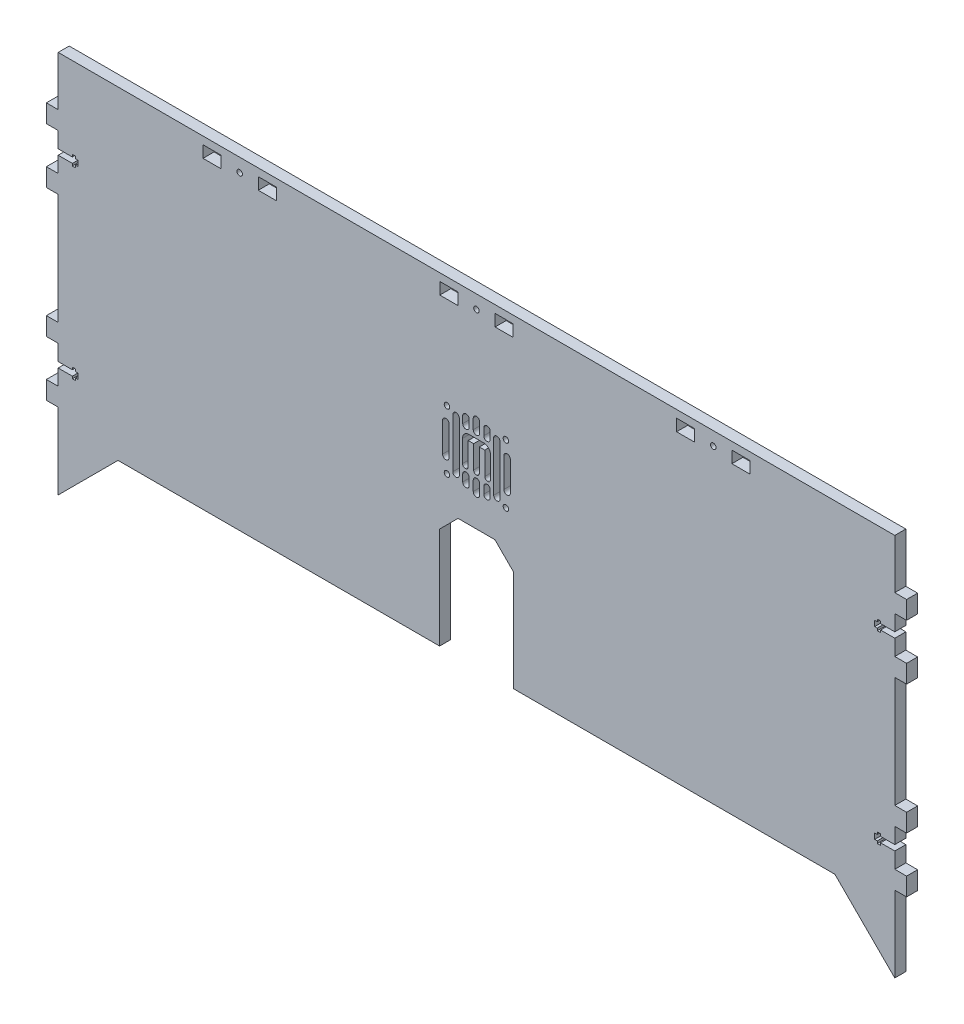
SolidWorks part; units mm, degrees
material "Acrylic (Medium-high impact)"
ref_plane "Front Plane" through (0, 0, 0) normal (0, 0, 1) x (1, 0, 0)
ref_plane "Top Plane" through (0, 0, 0) normal (0, 1, 0) x (1, 0, 0)
ref_plane "Right Plane" through (0, 0, 0) normal (1, 0, 0) x (0, 0, -1)
sketch "Sketch1" plane through (0, 0, 0) normal (0, 0, 1) x (1, 0, 0)
  line L0 (-200.4146, -68.906) -> (-25.9097, -68.906)
  line L1 (-200.4146, -68.906) -> (-232.9097, -101.4011)
  line L2 (-232.9097, 106.5989) -> (-232.9097, 79.6889)
  line L3 (-232.9097, 106.5989) -> (-117.9097, 106.5989)
  line L4 (106.0903, 106.5989) -> (221.0903, 106.5989)
  line L5 (221.0903, 39.8889) -> (221.0903, -20.3111)
  line L6 (-225.2097, 58.2882) -> (-232.9097, 58.2882)
  line L7 (-232.9097, 69.8889) -> (-232.9097, 61.2895)
  line L8 (-239.3097, 49.6889) -> (-239.3097, 39.8889)
  line L9 (-223.4097, 57.0395) -> (-223.4097, 58.2882)
  line L10 (-222.0097, 58.2882) -> (-223.4097, 58.2882)
  line L11 (-223.4097, 61.2895) -> (-223.4097, 62.5395)
  line L12 (-223.4097, 62.5395) -> (-225.2097, 62.5395)
  line L13 (-222.0097, 61.2895) -> (-223.4097, 61.2895)
  line L14 (-225.2097, 61.2895) -> (-232.9097, 61.2895)
  line L15 (-232.9097, 49.6889) -> (-239.3097, 49.6889)
  line L16 (-225.2097, 62.5395) -> (-225.2097, 61.2895)
  line L17 (-239.3097, 39.8889) -> (-232.9097, 39.8889)
  line L18 (-232.9097, 79.6889) -> (-239.3097, 79.6889)
  line L19 (-239.3097, 79.6889) -> (-239.3097, 69.8889)
  line L20 (-225.2097, 57.0395) -> (-225.2097, 58.2882)
  line L21 (-239.3097, 69.8889) -> (-232.9097, 69.8889)
  line L22 (-223.4097, 57.0395) -> (-225.2097, 57.0395)
  line L23 (-222.0097, 61.2895) -> (-222.0097, 58.2882)
  line L24 (-232.9097, 58.2882) -> (-232.9097, 49.6889)
  line L25 (-232.9097, -30.1111) -> (-232.9097, -38.7105)
  line L26 (-239.3097, -50.3111) -> (-239.3097, -60.1111)
  line L27 (-223.4097, -38.7105) -> (-223.4097, -37.4605)
  line L28 (-232.9097, -41.7118) -> (-232.9097, -50.3111)
  line L29 (-225.2097, -38.7105) -> (-232.9097, -38.7105)
  line L30 (-222.0097, -41.7118) -> (-223.4097, -41.7118)
  line L31 (-239.3097, -60.1111) -> (-232.9097, -60.1111)
  line L32 (-239.3097, -30.1111) -> (-232.9097, -30.1111)
  line L33 (-223.4097, -42.9605) -> (-225.2097, -42.9605)
  line L34 (-222.0097, -38.7105) -> (-222.0097, -41.7118)
  line L35 (-225.2097, -41.7118) -> (-232.9097, -41.7118)
  line L36 (-223.4097, -37.4605) -> (-225.2097, -37.4605)
  line L37 (-232.9097, -50.3111) -> (-239.3097, -50.3111)
  line L38 (-232.9097, -20.3111) -> (-239.3097, -20.3111)
  line L39 (-223.4097, -42.9605) -> (-223.4097, -41.7118)
  line L40 (-239.3097, -20.3111) -> (-239.3097, -30.1111)
  line L41 (4.0903, -3.906) -> (-15.9097, -3.906)
  line L42 (-15.9097, -3.906) -> (-25.9097, -13.906)
  line L43 (-25.9097, -13.906) -> (-25.9097, -68.906)
  line L44 (14.0903, -13.906) -> (14.0903, -68.906)
  line L45 (4.0903, -3.906) -> (14.0903, -13.906)
  line L46 (14.0903, -68.906) -> (188.5951, -68.906)
  line L47 (-225.2097, -37.4605) -> (-225.2097, -38.7105)
  line L48 (-225.2097, -42.9605) -> (-225.2097, -41.7118)
  line L49 (-222.0097, -38.7105) -> (-223.4097, -38.7105)
  line L50 (-232.9097, 39.8889) -> (-232.9097, -20.3111)
  line L51 (-232.9097, -60.1111) -> (-232.9097, -101.4011)
  line L52 (210.1903, -38.7105) -> (211.5903, -38.7105)
  line L53 (213.3903, -42.9605) -> (213.3903, -41.7118)
  line L54 (213.3903, -37.4605) -> (213.3903, -38.7105)
  line L55 (227.4903, -20.3111) -> (227.4903, -30.1111)
  line L56 (211.5903, -42.9605) -> (211.5903, -41.7118)
  line L57 (221.0903, -20.3111) -> (227.4903, -20.3111)
  line L58 (221.0903, -50.3111) -> (227.4903, -50.3111)
  line L59 (211.5903, -37.4605) -> (213.3903, -37.4605)
  line L60 (213.3903, -41.7118) -> (221.0903, -41.7118)
  line L61 (210.1903, -38.7105) -> (210.1903, -41.7118)
  line L62 (211.5903, -42.9605) -> (213.3903, -42.9605)
  line L63 (227.4903, -30.1111) -> (221.0903, -30.1111)
  line L64 (227.4903, -60.1111) -> (221.0903, -60.1111)
  line L65 (210.1903, -41.7118) -> (211.5903, -41.7118)
  line L66 (213.3903, -38.7105) -> (221.0903, -38.7105)
  line L67 (221.0903, -41.7118) -> (221.0903, -50.3111)
  line L68 (211.5903, -38.7105) -> (211.5903, -37.4605)
  line L69 (227.4903, -50.3111) -> (227.4903, -60.1111)
  line L70 (221.0903, -30.1111) -> (221.0903, -38.7105)
  line L71 (221.0903, 58.2882) -> (221.0903, 49.6889)
  line L72 (210.1903, 61.2895) -> (210.1903, 58.2882)
  line L73 (211.5903, 57.0395) -> (213.3903, 57.0395)
  line L74 (227.4903, 69.8889) -> (221.0903, 69.8889)
  line L75 (213.3903, 57.0395) -> (213.3903, 58.2882)
  line L76 (227.4903, 79.6889) -> (227.4903, 69.8889)
  line L77 (221.0903, 79.6889) -> (227.4903, 79.6889)
  line L78 (227.4903, 39.8889) -> (221.0903, 39.8889)
  line L79 (213.3903, 62.5395) -> (213.3903, 61.2895)
  line L80 (221.0903, 49.6889) -> (227.4903, 49.6889)
  line L81 (213.3903, 61.2895) -> (221.0903, 61.2895)
  line L82 (210.1903, 61.2895) -> (211.5903, 61.2895)
  line L83 (211.5903, 62.5395) -> (213.3903, 62.5395)
  line L84 (211.5903, 61.2895) -> (211.5903, 62.5395)
  line L85 (210.1903, 58.2882) -> (211.5903, 58.2882)
  line L86 (211.5903, 57.0395) -> (211.5903, 58.2882)
  line L87 (227.4903, 49.6889) -> (227.4903, 39.8889)
  line L88 (221.0903, 69.8889) -> (221.0903, 61.2895)
  line L89 (213.3903, 58.2882) -> (221.0903, 58.2882)
  line L90 (221.0903, 106.5989) -> (221.0903, 79.6889)
  line L91 (221.0903, -60.1111) -> (221.0903, -101.4011)
  line L92 (-114.5091, 102.4989) -> (-124.3091, 102.4989)
  line L93 (-124.3091, 96.0989) -> (-124.3091, 102.4989)
  line L94 (-144.5104, 96.0989) -> (-144.5104, 102.4989)
  line L95 (-154.3104, 96.0989) -> (-144.5104, 96.0989)
  line L96 (188.5951, -68.906) -> (221.0903, -101.4011)
  line L97 (-144.5104, 99.2989) -> (-124.3091, 99.2989) construction
  line L98 (-154.3104, 102.4989) -> (-144.5104, 102.4989)
  line L99 (91.0903, 106.5989) -> (106.0903, 106.5989)
  line L100 (-114.5091, 96.0989) -> (-124.3091, 96.0989)
  line L101 (-149.4104, 102.4989) -> (-149.4104, 96.0989) construction
  line L102 (-114.5091, 96.0989) -> (-114.5091, 102.4989)
  line L103 (-102.9097, 106.5989) -> (-117.9097, 106.5989)
  line L104 (9.0909, 102.4989) -> (9.0909, 96.0989) construction
  line L105 (-20.9104, 102.4989) -> (-20.9104, 96.0989) construction
  line L106 (-25.8104, 96.0989) -> (-16.0104, 96.0989)
  line L107 (4.1909, 96.0989) -> (4.1909, 102.4989)
  line L108 (-25.8104, 102.4989) -> (-16.0104, 102.4989)
  line L109 (13.9909, 96.0989) -> (13.9909, 102.4989)
  line L110 (-16.0104, 99.2989) -> (4.1909, 99.2989) construction
  line L111 (-25.8104, 96.0989) -> (-25.8104, 102.4989)
  line L112 (-16.0104, 96.0989) -> (-16.0104, 102.4989)
  line L113 (13.9909, 102.4989) -> (4.1909, 102.4989)
  line L114 (13.9909, 96.0989) -> (4.1909, 96.0989)
  line L115 (-119.4091, 102.4989) -> (-119.4091, 96.0989) construction
  line L116 (10.0903, 46.0332) -> (-21.9097, 14.0332) construction
  line L117 (-102.9097, 106.5989) -> (91.0903, 106.5989)
  line L118 (0.0957, 21.5206) -> (0.1807, 21.5207)
  line L119 (-154.3104, 96.0989) -> (-154.3104, 102.4989)
  line L120 (142.4909, 102.4989) -> (132.6909, 102.4989)
  line L121 (132.6909, 96.0989) -> (132.6909, 102.4989)
  line L122 (112.4896, 96.0989) -> (112.4896, 102.4989)
  line L123 (102.6896, 96.0989) -> (112.4896, 96.0989)
  line L124 (112.4896, 99.2989) -> (132.6909, 99.2989) construction
  line L125 (102.6896, 102.4989) -> (112.4896, 102.4989)
  line L126 (142.4909, 96.0989) -> (132.6909, 96.0989)
  line L127 (107.5896, 102.4989) -> (107.5896, 96.0989) construction
  line L128 (142.4909, 96.0989) -> (142.4909, 102.4989)
  line L129 (137.5909, 102.4989) -> (137.5909, 96.0989) construction
  line L130 (-5.9543, 21.5205) -> (-5.8693, 21.5207)
  line L131 (102.6896, 96.0989) -> (102.6896, 102.4989)
  line L132 (-187.7413, -57.4543) -> (-183.9913, -57.4543) construction
  line L133 (-181.4913, -57.4543) -> (-181.4913, -57.0156) construction
  line L134 (-183.9913, -57.0156) -> (-183.9913, -57.4543) construction
  line L136 (-7.4666, 35.4359) -> (-7.4666, 23.0332)
  line L137 (-13.5166, 23.0334) -> (-13.5166, 34.8729)
  line L138 (-12.0043, 21.5207) -> (-11.9193, 21.5209)
  line L139 (1.6929, 23.0334) -> (1.6929, 34.8729)
  line L143 (-9.8747, 18.2689) -> (-9.8747, 14.4689)
  line L144 (-13.3747, 14.4689) -> (-13.3747, 18.2689)
  line L145 (1.5552, 14.4689) -> (1.5552, 18.2689)
  line L146 (-1.9448, 18.2689) -> (-1.9448, 14.4689)
  line L148 (-1.9793, 38.5452) -> (-9.8443, 38.5452)
  line L149 (-1.4166, 35.4359) -> (-1.4166, 23.0332)
  line L151 (-10.4071, 23.0336) -> (-10.4071, 35.4359)
  line L152 (-7.4666, 35.4359) -> (-10.4071, 35.4359)
  line L153 (-4.3571, 23.0334) -> (-4.3571, 35.4359)
  line L154 (-4.3571, 35.4359) -> (-1.4166, 35.4359)
  line L155 (-7.6597, 18.2689) -> (-7.6597, 12.844)
  line L156 (-4.1597, 18.2689) -> (-4.1597, 12.844)
  line L157 (12.4682, 38.0475) -> (12.4682, 22.1189)
  line L158 (3.4242, 16.6189) -> (3.4242, 43.5475)
  line L159 (-5.9097, 41.8975) -> (-5.9097, 18.2689) construction
  line L160 (-15.4963, 30.0832) -> (3.6769, 30.0832) construction
  line L161 (-5.9077, 21.5212) -> (-5.9118, 38.5452) construction
  line L162 (-24.2877, 38.0475) -> (-24.2877, 22.1189)
  line L163 (-20.7877, 22.1189) -> (-20.7877, 38.0475)
  line L164 (-4.1597, 41.8975) -> (-4.1597, 47.3224)
  line L165 (6.9242, 43.5475) -> (6.9242, 16.6189)
  line L166 (8.9682, 22.1189) -> (8.9682, 38.0475)
  line L167 (-7.6597, 41.8975) -> (-7.6597, 47.3224)
  line L168 (-1.9448, 41.8975) -> (-1.9448, 45.6975)
  line L169 (-18.7437, 43.5475) -> (-18.7437, 16.6189)
  line L170 (1.5552, 45.6975) -> (1.5552, 41.8975)
  line L171 (-13.3747, 45.6975) -> (-13.3747, 41.8975)
  line L172 (-9.8747, 41.8975) -> (-9.8747, 45.6975)
  line L173 (-15.2437, 16.6189) -> (-15.2437, 43.5475)
  circle A0 centre (-134.4097, 99.2989) radius 1.5
  circle A1 centre (122.5903, 99.2989) radius 1.5
  circle A2 centre (-21.9097, 46.0332) radius 1.5
  circle A3 centre (-5.9097, 99.2989) radius 1.5
  arc A4 (-181.4913, -57.0156) -> (-183.9913, -57.0156) centre (-182.7413, -55.4543) ccw construction
  circle A5 centre (10.0903, 46.0332) radius 1.5
  circle A6 centre (10.0903, 14.0332) radius 1.5
  circle A7 centre (-21.9097, 14.0332) radius 1.5
  arc A8 (3.4242, 43.5475) -> (6.9242, 43.5475) centre (5.1742, 43.5475) cw
  arc A9 (8.9682, 38.0475) -> (12.4682, 38.0475) centre (10.7182, 38.0475) cw
  arc A14 (8.9682, 22.1189) -> (12.4682, 22.1189) centre (10.7182, 22.1189) ccw
  arc A15 (3.4242, 16.6189) -> (6.9242, 16.6189) centre (5.1742, 16.6189) ccw
  arc A16 (-9.8747, 18.2689) -> (-13.3747, 18.2689) centre (-11.6247, 18.2689) ccw
  arc A17 (-13.3747, 14.4689) -> (-9.8747, 14.4689) centre (-11.6247, 14.4689) ccw
  arc A18 (1.5552, 14.4689) -> (-1.9448, 14.4689) centre (-0.1948, 14.4689) cw
  arc A19 (-15.2437, 43.5475) -> (-18.7437, 43.5475) centre (-16.9937, 43.5475) ccw
  arc A20 (-20.7877, 38.0475) -> (-24.2877, 38.0475) centre (-22.5377, 38.0475) ccw
  arc A21 (-20.7877, 22.1189) -> (-24.2877, 22.1189) centre (-22.5377, 22.1189) cw
  arc A22 (-7.6597, 41.8975) -> (-4.1597, 41.8975) centre (-5.9097, 41.8975) ccw
  arc A23 (-4.1597, 47.3224) -> (-7.6597, 47.3224) centre (-5.9097, 47.3224) ccw
  arc A24 (-1.9448, 41.8975) -> (1.5552, 41.8975) centre (-0.1948, 41.8975) ccw
  arc A25 (1.5552, 45.6975) -> (-1.9448, 45.6975) centre (-0.1948, 45.6975) ccw
  arc A26 (-13.3747, 45.6975) -> (-9.8747, 45.6975) centre (-11.6247, 45.6975) cw
  arc A27 (-15.2437, 16.6189) -> (-18.7437, 16.6189) centre (-16.9937, 16.6189) cw
  arc A28 (-9.8747, 41.8975) -> (-13.3747, 41.8975) centre (-11.6247, 41.8975) cw
  arc A29 (-1.9448, 18.2689) -> (1.5552, 18.2689) centre (-0.1948, 18.2689) cw
  arc A31 (1.6929, 34.8729) -> (-1.9793, 38.5452) centre (-1.9793, 34.8729) ccw
  arc A32 (-4.1597, 12.844) -> (-7.6597, 12.844) centre (-5.9097, 12.844) cw
  arc A33 (-7.6597, 18.2689) -> (-4.1597, 18.2689) centre (-5.9097, 18.2689) cw
  arc A36 (-9.8443, 38.5452) -> (-13.5166, 34.8729) centre (-9.8443, 34.8729) ccw
  ellipse E0 centre (0.1802, 23.0334) end of major axis (1.2499, 21.9637) minor radius 1.5126 (0.1807, 21.5207) -> (1.6929, 23.0334) ccw
  ellipse E1 centre (-5.9538, 23.0332) end of major axis (-7.0235, 21.9635) minor radius 1.5127 (-7.4666, 23.0332) -> (-5.9543, 21.5205) ccw
  ellipse E2 centre (-5.8698, 23.0334) end of major axis (-4.8, 21.9637) minor radius 1.5126 (-5.8693, 21.5207) -> (-4.3571, 23.0334) ccw
  ellipse E3 centre (-12.0038, 23.0334) end of major axis (-13.0736, 21.9637) minor radius 1.5126 (-13.5166, 23.0334) -> (-12.0043, 21.5207) ccw
  ellipse E4 centre (0.0962, 23.0333) end of major axis (-0.9736, 21.9636) minor radius 1.5126 (-1.4166, 23.0332) -> (0.0957, 21.5206) ccw
  ellipse E5 centre (-11.9198, 23.0336) end of major axis (-10.8501, 21.9639) minor radius 1.5126 (-11.9193, 21.5209) -> (-10.4071, 23.0336) ccw
  dimension "D1" = 26.91
  dimension "D3" = 10
  dimension "D4" = 135
  dimension "D5" = 135
  dimension "D6" = 10
extrude "Boss-Extrude1" add sketch "Sketch1" along normal blind 6
